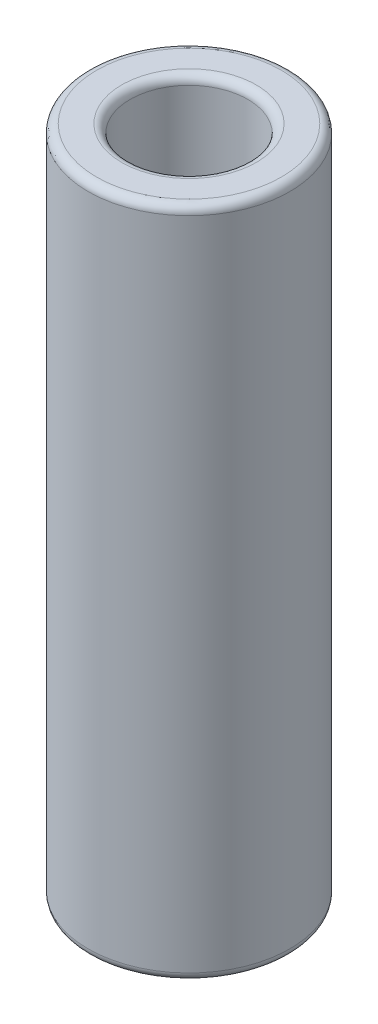
SolidWorks part; units mm, degrees
ref_plane "Płaszczyzna przednia" through (0, 0, 0) normal (0, 0, 1) x (1, 0, 0)
ref_plane "Płaszczyzna górna" through (0, 0, 0) normal (0, 1, 0) x (1, 0, 0)
ref_plane "Płaszczyzna prawa" through (0, 0, 0) normal (1, 0, 0) x (0, 0, -1)
sketch "Szkic3" plane through (0, 0, 0) normal (0, 1, 0) x (1, 0, 0)
  circle A0 centre (0, 0) radius 3.5
  circle A1 centre (0, 0) radius 6
  dimension "D1" = 12
  dimension "D2" = 7
extrude "Dodanie-wyciągnięcie1" add sketch "Szkic3" along normal blind 40
fillet "Zaokrąglenie1" radius 0.5 2 edges at (0, 40, 3.5) (0, 40, 6)
fillet "Zaokrąglenie2" radius 0.5 2 edges at (0, 0, 3.5) (0, 0, 6)
